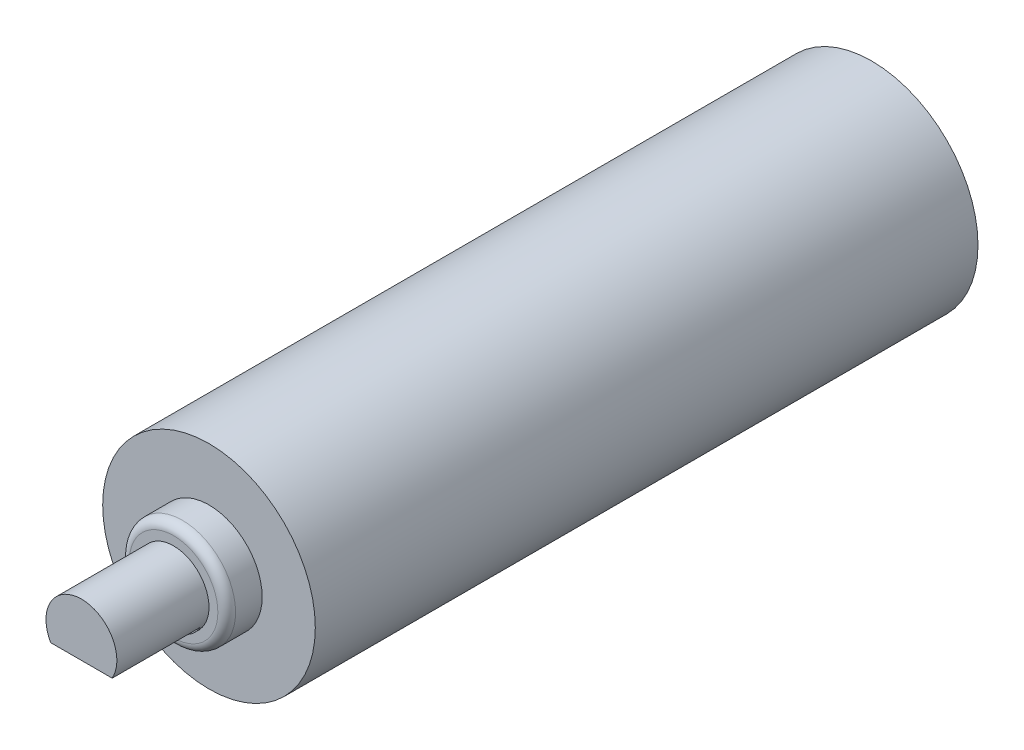
SolidWorks part; units mm, degrees
material "0.7033 (EN-GJS-350-22-LT)"
ref_plane "前视基准面" through (0, 0, 0) normal (0, 0, 1) x (1, 0, 0)
ref_plane "上视基准面" through (0, 0, 0) normal (0, 1, 0) x (1, 0, 0)
ref_plane "右视基准面" through (0, 0, 0) normal (1, 0, 0) x (0, 0, -1)
sketch "草图1" plane through (0, 0, 0) normal (0, 0, 1) x (1, 0, 0)
  circle A0 centre (0, 0) radius 3
  dimension "D1" = 6
extrude "凸台-拉伸1" add sketch "草图1" against normal blind 18.7
sketch "草图2" plane through (0, 0, 0) normal (0, 0, 1) x (1, 0, 0)
  circle A0 centre (0, 0) radius 1.5
  dimension "D1" = 3
extrude "凸台-拉伸2" add sketch "草图2" along normal blind 1
sketch "草图3" plane through (0, 0, 1) normal (0, 0, 1) x (1, 0, 0)
  circle A0 centre (0, 0) radius 1
  dimension "D1" = 2
extrude "凸台-拉伸3" add sketch "草图3" along normal blind 2.6
sketch "草图4" plane through (0, 0, 3.6) normal (0, 0, 1) x (1, 0, 0)
  line L0 (0, 1) -> (0, -0.5) construction
  line L2 (0, -0.5) -> (0.8625, -0.5)
  line L4 (0, -1) -> (0.8625, -1)
  line L5 (0.8625, -0.5) -> (0.8625, -1)
  line L6 (0, -0.5) -> (-0.8694, -0.5)
  line L8 (0, -1) -> (-0.8694, -1)
  line L9 (-0.8694, -0.5) -> (-0.8694, -1)
  circle A0 centre (0, 0) radius 1 construction
  circle A1 centre (0, 0) radius 1 construction
  dimension "D1" = 1.5
extrude "切除-拉伸1" cut sketch "草图4" against normal blind 2.5
fillet "圆角1" radius 0.25 1 edges at (1.5, 0, 1)
